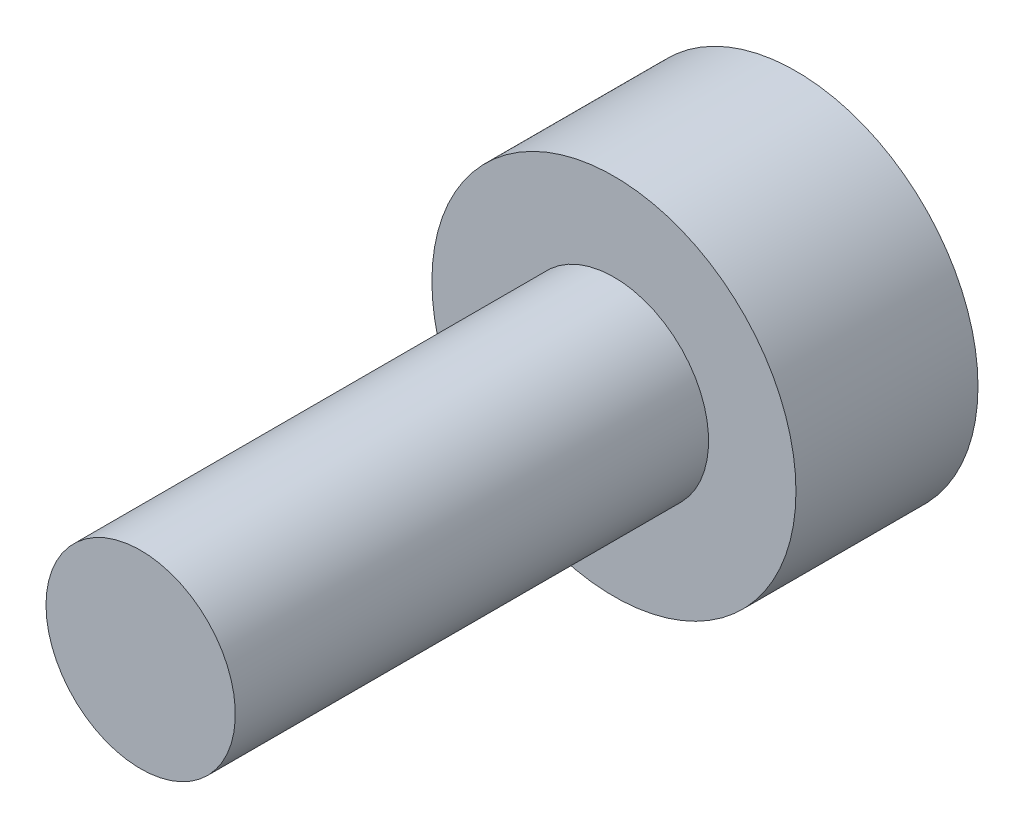
SolidWorks part; units mm, degrees
ref_plane "Front Plane" through (0, 0, 0) normal (0, 0, 1) x (1, 0, 0)
ref_plane "Top Plane" through (0, 0, 0) normal (0, 1, 0) x (1, 0, 0)
ref_plane "Right Plane" through (0, 0, 0) normal (1, 0, 0) x (0, 0, -1)
sketch "Sketch1" plane through (0, 0, 0) normal (0, 0, 1) x (1, 0, 0)
  circle A0 centre (0, 0) radius 2.6
  dimension "D1" = 5.2
extrude "Boss-Extrude1" add sketch "Sketch1" along normal blind 13
sketch "Sketch2" plane through (0, 0, 0) normal (0, 0, -1) x (-1, 0, 0)
  circle A0 centre (0, 0) radius 5
  dimension "D1" = 10
extrude "Boss-Extrude2" add sketch "Sketch2" along normal blind 5
